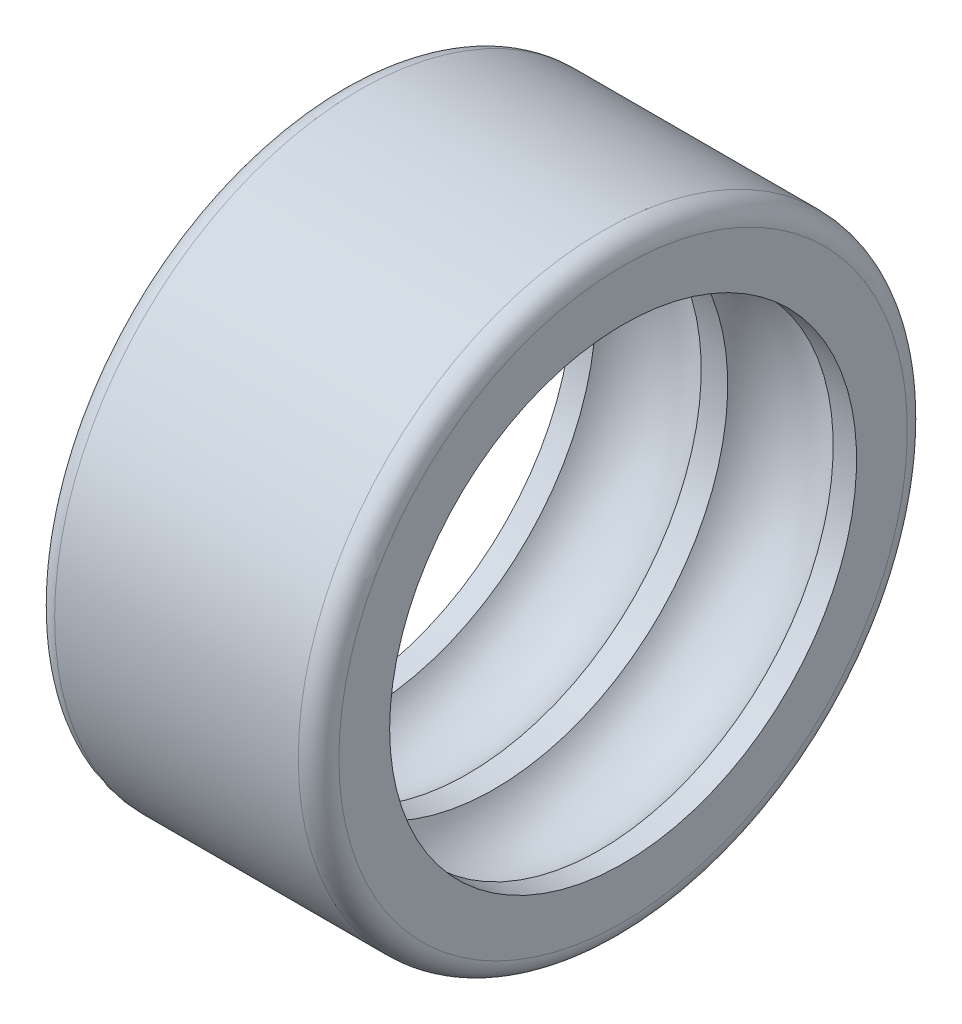
SolidWorks part; units mm, degrees
ref_plane "Plan1" through (0, 0, 0) normal (0, 0, 1) x (1, 0, 0)
ref_plane "Plan2" through (0, 0, 0) normal (0, 1, 0) x (1, 0, 0)
ref_plane "Plan3" through (0, 0, 0) normal (1, 0, 0) x (0, 0, -1)
sketch "Esquisse1" plane through (0, 0, 0) normal (0, 0, 1) x (1, 0, 0)
  line L0 (0, 11.5) -> (0, 15)
  line L1 (0, 15) -> (14, 15)
  line L2 (14, 15) -> (14, 11.5)
  line L3 (14, 11.5) -> (12.8481, 11.5)
  line L4 (13, 5) -> (1, 5) construction
  line L5 (0, 8.5) -> (0, -8.5) construction
  line L6 (7.6519, 11.5) -> (6.3481, 11.5)
  line L7 (1.1519, 11.5) -> (0, 11.5)
  line L8 (0, 0) -> (17.7699, 0) construction
  line L9 (0, 0) -> (30.1449, 0) construction
  arc A0 (6.3481, 11.5) -> (1.1519, 11.5) centre (3.75, 10) ccw
  arc A1 (12.8481, 11.5) -> (7.6519, 11.5) centre (10.25, 10) ccw
  arc A2 (7.6519, 8.5) -> (12.8481, 8.5) centre (10.25, 10) ccw construction
  arc A3 (1.1519, 8.5) -> (6.3481, 8.5) centre (3.75, 10) ccw construction
  dimension "D1" = 10
  dimension "D2" = 14
  dimension "D3" = 3.5
revolve "Base-Révolution" add sketch "Esquisse1" angle 360 about L8
fillet "Congé1" radius 1 2 edges at (0, 0, 15) (14, 0, 15)
sketch "Esquisse2" [suppressed] plane through (0, 0, 0) normal (0, 1, 0) x (1, 0, 0)
  point P7 (7, 0)
